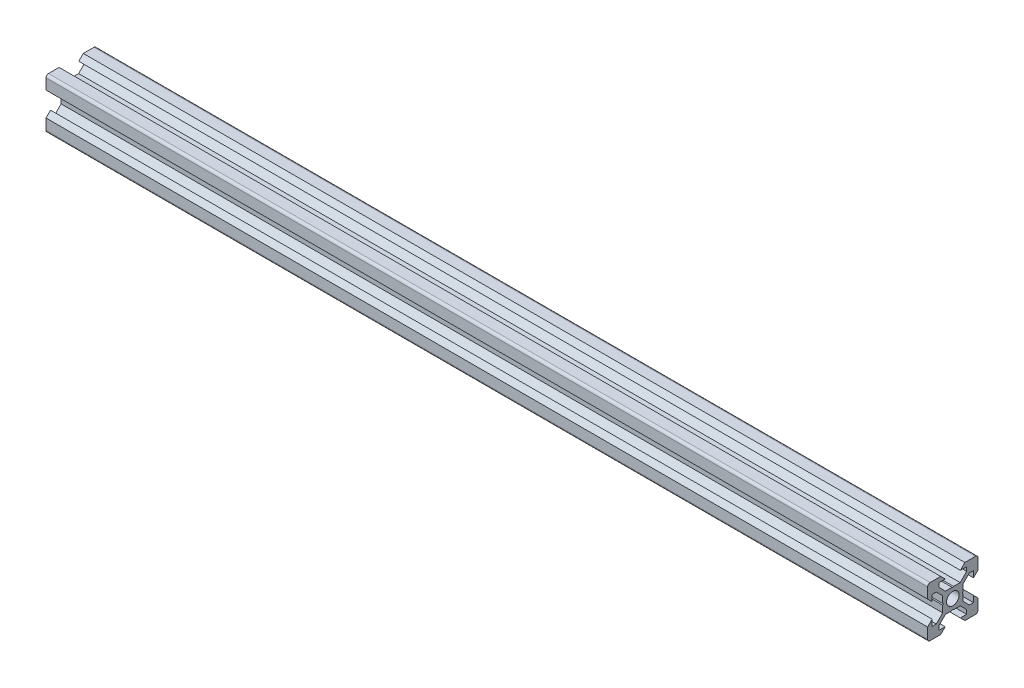
SolidWorks part; units mm, degrees
material "6063-T5"
material "6063-T5"
ref_plane "Plano frontal" through (0, 0, 0) normal (0, 0, 1) x (1, 0, 0)
ref_plane "Plano superior" through (0, 0, 0) normal (0, 1, 0) x (1, 0, 0)
ref_plane "Plano direito" through (0, 0, 0) normal (1, 0, 0) x (0, 0, -1)
sketch "Esboço1" plane through (0, 0, 0) normal (0, 0, 1) x (1, 0, 0)
  line L0 (0, 0) -> (350, 0)
  dimension "D1" = 350
other " C:\\USERS\\USER\\GOOGLE DRIVE\\13. INFORMAÇÕES TÉCNICAS\\BIBLIOTECA SERVIDOR\\PERFIS DE SOLDAGEM\\PERFIL ALUMÍNIO\\QUADRADO\\PF20-11 - PERFIL 2020 V-SLOT - IS MISSING(1)"
ref_plane "Plano1" through (0, 0, 0) normal (1, 0, 0) x (0, 1, 0)
sketch "Sketch11" plane through (0, 0, 0) normal (1, 0, 0) x (0, 1, 0)
  line L0 (-4.8, 10) -> (-3, 8.2)
  line L1 (-3, 8.2) -> (-5.5, 8.2)
  line L2 (-5.5, 8.2) -> (-5.5, 6.5607)
  line L3 (-5.5, 6.5607) -> (-2.9393, 4)
  line L4 (-2.9393, 4) -> (-0.3, 4)
  line L5 (5.5, 6.5607) -> (2.9393, 4)
  line L6 (5.5, 8.2) -> (5.5, 6.5607)
  line L7 (3, 8.2) -> (5.5, 8.2)
  line L8 (4.8, 10) -> (3, 8.2)
  line L9 (-0.3, 4) -> (0, 3.7)
  line L10 (0.3, 4) -> (0, 3.7)
  line L11 (0.3, 4) -> (2.9393, 4)
  line L12 (9, 10) -> (4.8, 10)
  line L13 (10, 4.8) -> (8.2, 3)
  line L14 (10, 4.8) -> (10, 9)
  line L15 (8.2, 3) -> (8.2, 5.5)
  line L16 (8.2, 5.5) -> (6.5607, 5.5)
  line L17 (6.5607, 5.5) -> (4, 2.9393)
  line L18 (4.8, -10) -> (3, -8.2)
  line L19 (3, -8.2) -> (5.5, -8.2)
  line L20 (5.5, -8.2) -> (5.5, -6.5607)
  line L21 (5.5, -6.5607) -> (2.9393, -4)
  line L22 (2.9393, -4) -> (0.3, -4)
  line L23 (0.3, -4) -> (0, -3.7)
  line L24 (-0.3, -4) -> (0, -3.7)
  line L25 (-0.3, -4) -> (-2.9393, -4)
  line L26 (-5.5, -6.5607) -> (-2.9393, -4)
  line L27 (-5.5, -8.2) -> (-5.5, -6.5607)
  line L28 (-3, -8.2) -> (-5.5, -8.2)
  line L29 (-4.8, -10) -> (-3, -8.2)
  line L30 (-10, -4.8) -> (-10, -9)
  line L31 (-10, -4.8) -> (-8.2, -3)
  line L32 (-8.2, -3) -> (-8.2, -5.5)
  line L33 (-8.2, -5.5) -> (-6.5607, -5.5)
  line L34 (-6.5607, -5.5) -> (-4, -2.9393)
  line L35 (-4, -2.9393) -> (-4, -0.3)
  line L36 (-4, -0.3) -> (-3.7, 0)
  line L37 (-4, 0.3) -> (-3.7, 0)
  line L38 (-4, 0.3) -> (-4, 2.9393)
  line L39 (-6.5607, 5.5) -> (-4, 2.9393)
  line L40 (-8.2, 5.5) -> (-6.5607, 5.5)
  line L41 (-8.2, 3) -> (-8.2, 5.5)
  line L42 (-10, 4.8) -> (-8.2, 3)
  line L43 (-4.8, 10) -> (-9, 10)
  line L44 (4, 2.9393) -> (4, 0.3)
  line L45 (4, 0.3) -> (3.7, 0)
  line L46 (4, -0.3) -> (3.7, 0)
  line L47 (4, -0.3) -> (4, -2.9393)
  line L48 (6.5607, -5.5) -> (4, -2.9393)
  line L49 (8.2, -5.5) -> (6.5607, -5.5)
  line L50 (8.2, -3) -> (8.2, -5.5)
  line L51 (10, -4.8) -> (8.2, -3)
  line L52 (10, -9) -> (10, -4.8)
  line L53 (4.8, -10) -> (9, -10)
  line L106 (-10, 9) -> (-10, 4.8)
  line L107 (-9, -10) -> (-4.8, -10)
  arc A0 (10, 9) -> (9, 10) centre (9, 9) ccw
  arc A1 (9, -10) -> (10, -9) centre (9, -9) ccw
  arc A3 (-10, -9) -> (-9, -10) centre (-9, -9) ccw
  arc A4 (-9, 10) -> (-10, 9) centre (-9, 9) ccw
  circle A7 centre (0, 0) radius 2.5
  point P1 (-10, 10)
  point P3 (10, 10)
  point P4 (10, -10)
  point P68 (0, 0)
  point P70 (10, 0)
  point P71 (0, 0)
  point P72 (0, 0)
  point P113 (0, -10)
  point P114 (-10, -10)
  point P115 (-10, 0)
  point P116 (0, 10)
  point P118 (0, 0)
